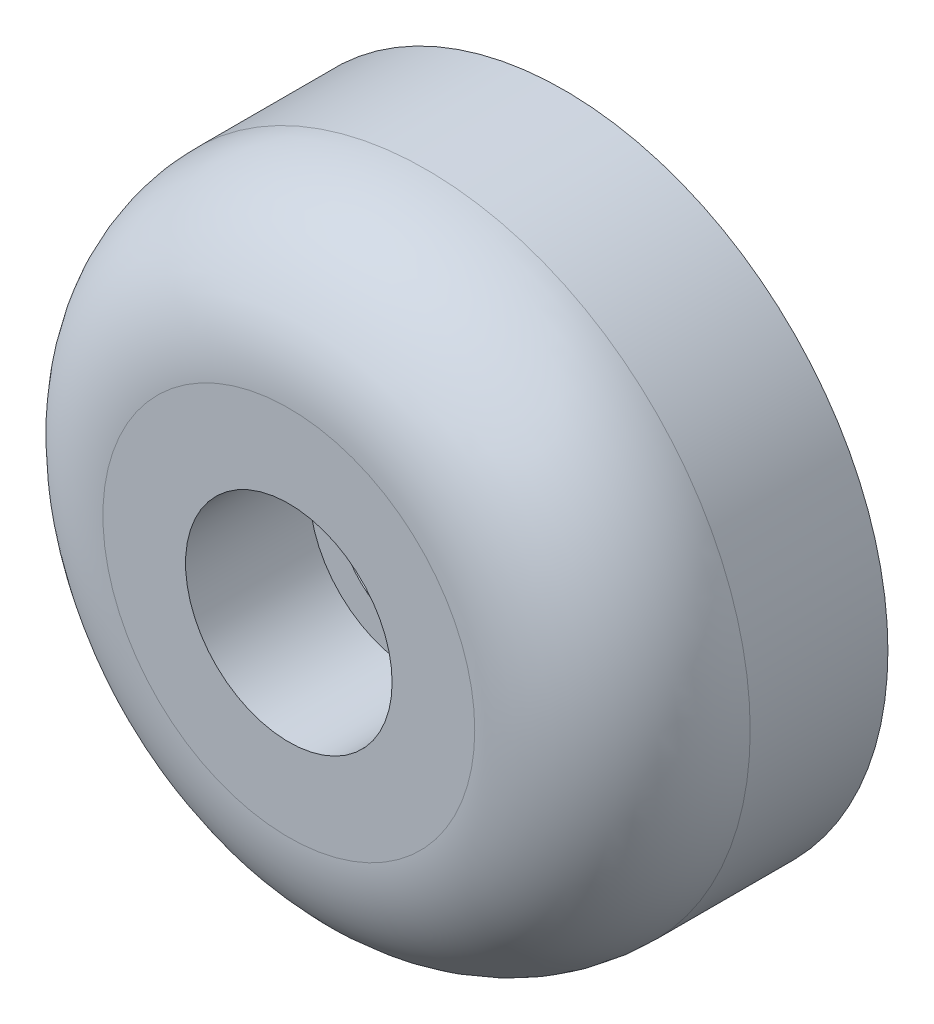
SolidWorks part; units mm, degrees
ref_plane "Спереди" through (0, 0, 0) normal (0, 0, 1) x (1, 0, 0)
ref_plane "Сверху" through (0, 0, 0) normal (0, 1, 0) x (1, 0, 0)
ref_plane "Справа" through (0, 0, 0) normal (1, 0, 0) x (0, 0, -1)
other "Configuration Table"
sketch "Эскиз2" plane through (0, 0, 0) normal (0, 0, 1) x (1, 0, 0)
  circle A0 centre (0, 0) radius 23.5
  dimension "D1" = 47
extrude "Бобышка-Вытянуть1" add sketch "Эскиз2" along normal blind 20
fillet "Скругление3" radius 10 1 edges at (23.5, 0, 20)
shell "Оболочка2" thickness 2
sketch "Эскиз5" plane through (0, 0, 18) normal (0, 0, -1) x (-1, 0, 0)
  circle A0 centre (0, 0) radius 9.5
  dimension "D1" = 19
extrude "Бобышка-Вытянуть2" add sketch "Эскиз5" along normal blind 18
sketch "Эскиз6" plane through (0, 0, 0) normal (0, 0, -1) x (-1, 0, 0)
  circle A0 centre (0, 0) radius 2.4
  dimension "D1" = 4.8
extrude "Вырез-Вытянуть1" cut sketch "Эскиз6" against normal through all
sketch "Эскиз7" plane through (0, 0, 0) normal (0, 0, -1) x (-1, 0, 0)
  line L0 (0, 29.4416) -> (0, -31.5446) construction
  line L1 (-0.6, 8.9376) -> (-0.6, 21.9376)
  line L2 (-0.6, 21.9376) -> (0.6, 21.9376)
  line L3 (0.6, 21.9376) -> (0.6, 8.9376)
  line L4 (0.6, 8.9376) -> (-0.6, 8.9376)
  line L5 (7.4402, 4.9884) -> (18.6985, 11.4884)
  line L6 (8.0402, 3.9492) -> (7.4402, 4.9884)
  line L7 (18.6985, 11.4884) -> (19.2985, 10.4492)
  line L8 (19.2985, 10.4492) -> (8.0402, 3.9492)
  line L9 (8.0402, -3.9492) -> (19.2985, -10.4492)
  line L10 (7.4402, -4.9884) -> (8.0402, -3.9492)
  line L11 (19.2985, -10.4492) -> (18.6985, -11.4884)
  line L12 (18.6985, -11.4884) -> (7.4402, -4.9884)
  line L13 (0.6, -8.9376) -> (0.6, -21.9376)
  line L14 (-0.6, -8.9376) -> (0.6, -8.9376)
  line L15 (0.6, -21.9376) -> (-0.6, -21.9376)
  line L16 (-0.6, -21.9376) -> (-0.6, -8.9376)
  line L17 (-7.4402, -4.9884) -> (-18.6985, -11.4884)
  line L18 (-8.0402, -3.9492) -> (-7.4402, -4.9884)
  line L19 (-18.6985, -11.4884) -> (-19.2985, -10.4492)
  line L20 (-19.2985, -10.4492) -> (-8.0402, -3.9492)
  line L21 (-8.0402, 3.9492) -> (-19.2985, 10.4492)
  line L22 (-7.4402, 4.9884) -> (-8.0402, 3.9492)
  line L23 (-19.2985, 10.4492) -> (-18.6985, 11.4884)
  line L24 (-18.6985, 11.4884) -> (-7.4402, 4.9884)
  circle A0 centre (0, 0) radius 23.5 construction
  point P32 (0, 0)
  dimension "D4" = 21.9376
  dimension "D1" = 1.2
  dimension "D2" = 0.6
  dimension "D3" = 13
  dimension "D5" = 6
extrude "Бобышка-Вытянуть3" add sketch "Эскиз7" against normal up to body
sketch "Эскиз8" plane through (0, 0, 20) normal (0, 0, 1) x (1, 0, 0)
  circle A0 centre (0, 0) radius 7.5
  dimension "D1" = 15
extrude "Вырез-Вытянуть2" cut sketch "Эскиз8" against normal blind 9
chamfer "Фаска1" distance 3 angle 45 1 edges at (2.4, 0, 11)
